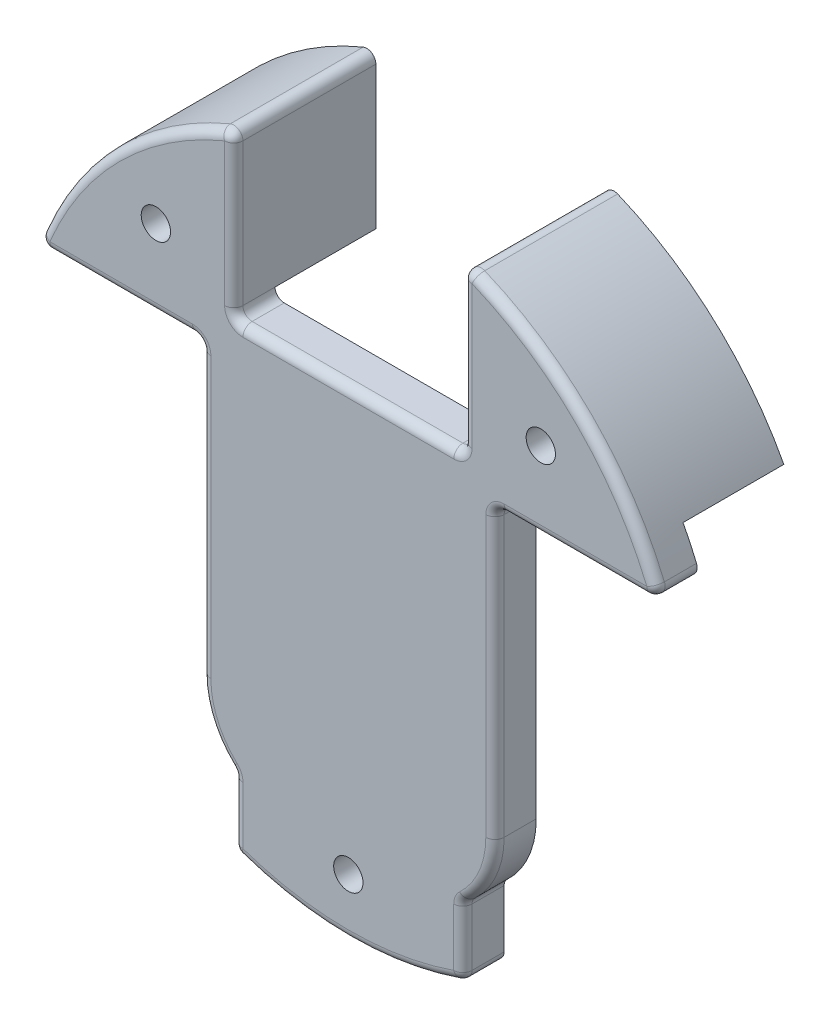
SolidWorks part; units mm, degrees
ref_plane "Front Plane" through (0, 0, 0) normal (0, 0, 1) x (1, 0, 0)
ref_plane "Top Plane" through (0, 0, 0) normal (0, 1, 0) x (1, 0, 0)
ref_plane "Right Plane" through (0, 0, 0) normal (1, 0, 0) x (0, 0, -1)
sketch "草图1" plane through (0, 0, 0) normal (0, 0, 1) x (1, 0, 0)
  circle A0 centre (0, 0) radius 36.25
extrude "凸台-拉伸1" add sketch "草图1" along normal blind 10
sketch "草图2" plane through (0, 0, 0) normal (0, 0, 1) x (1, 0, 0)
  line L1 (-12.5, 36.25) -> (12.5, 36.25)
  line L2 (-12.5, 36.25) -> (-12.5, 16)
  line L3 (-12.5, 16) -> (12.5, 16)
  line L4 (12.5, 36.25) -> (12.5, 16)
extrude "切除-拉伸1" cut sketch "草图2" along normal blind 4.5
sketch "草图3" plane through (0, 0, 0) normal (0, 0, 1) x (1, 0, 0)
  line L1 (-36.25, 12.5) -> (-12.5, 12.5)
  line L2 (-36.25, 12.5) -> (-36.25, -36.25)
  line L3 (-36.25, -36.25) -> (-12.5, -36.25)
  line L4 (-12.5, 12.5) -> (-12.5, -36.25)
  line L5 (12.5, 12.5) -> (36.25, 12.5)
  line L6 (12.5, 12.5) -> (12.5, -36.25)
  line L7 (12.5, -36.25) -> (36.25, -36.25)
  line L8 (36.25, 12.5) -> (36.25, -36.25)
extrude "切除-拉伸2" cut sketch "草图3" along normal blind 4.5
sketch "草图4" plane through (0, 0, 0) normal (0, 0, 1) x (1, 0, 0)
  circle A0 centre (-6, -19) radius 10
extrude "凸台-拉伸2" add sketch "草图4" along normal blind 4.5
sketch "草图5" plane through (0, 0, 0) normal (0, 0, 1) x (1, 0, 0)
  circle A0 centre (6, -19) radius 10
extrude "凸台-拉伸3" add sketch "草图5" along normal blind 4.5
sketch "草图6" plane through (0, 0, 0) normal (0, 0, 1) x (1, 0, 0)
  line L1 (-16, -19) -> (16, -19)
  line L2 (-16, -19) -> (-16, 12.5)
  line L3 (-16, 12.5) -> (16, 12.5)
  line L4 (16, -19) -> (16, 12.5)
extrude "凸台-拉伸4" add sketch "草图6" along normal blind 4.5
sketch "草图7" plane through (0, 0, 4.5) normal (0, 0, -1) x (-1, 0, 0)
  circle A0 centre (0, 0) radius 36.25
extrude "切除-拉伸3" cut sketch "草图7" against normal blind 5.5
sketch "草图8" plane through (0, 0, 0) normal (0, 0, 1) x (1, 0, 0)
  line L1 (-36.25, 17) -> (-12.5, 17)
  line L2 (-36.25, 17) -> (-36.25, 36.25)
  line L3 (-36.25, 36.25) -> (-12.5, 36.25)
  line L4 (-12.5, 17) -> (-12.5, 36.25)
  line L9 (12.5, 17) -> (36.25, 17)
  line L10 (12.5, 17) -> (12.5, 36.25)
  line L11 (12.5, 36.25) -> (36.25, 36.25)
  line L12 (36.25, 17) -> (36.25, 36.25)
extrude "凸台-拉伸5" add sketch "草图8" against normal blind 11
sketch "草图9" plane through (0, 0, 0) normal (0, 0, 1) x (1, 0, 0)
  circle A0 centre (0, 0) radius 36.25
extrude "切除-拉伸4" cut sketch "草图9" against normal blind 11 flip side to cut contours A0
sketch "草图10" plane through (0, 0, 4.5) normal (0, 0, 1) x (1, 0, 0)
  circle A0 centre (-21, 21) radius 0.8
  circle A1 centre (21, 21) radius 0.8
  circle A2 centre (0, -30) radius 0.8
hole_wizard "孔1" positions "草图11" profile "草图12" legacy
sketch "草图11" plane through (0, 0, 4.5) normal (0, 0, 1) x (1, 0, 0)
  point P0 (-21, 21)
  point P3 (21, 21)
sketch "草图12" plane through (-21, 21, 4.5) normal (1, 0, 0) x (0, -1, 0)
  line L0 (0, 0) -> (0, 100)
  line L1 (0, 100) -> (0.8, 100)
  line L2 (0.8, 100) -> (0.8, 14.1)
  line L3 (0.8, 14.1) -> (1.6, 14.1)
  line L4 (1.6, 14.1) -> (1.6, 0)
  line L5 (1.6, 0) -> (0, 0)
  line L6 (0, 110) -> (0, -10) construction
  dimension "直径" = 1.6
  dimension "深度" = 100
  dimension "柱坑直径" = 3.2
  dimension "柱坑深度" = 14.1
hole_wizard "孔2" positions "草图13" profile "草图14" legacy
sketch "草图13" plane through (0, 0, 4.5) normal (0, 0, 1) x (1, 0, 0)
  point P0 (0, -30)
sketch "草图14" plane through (0, -30, 4.5) normal (1, 0, 0) x (0, -1, 0)
  line L0 (0, 0) -> (0, 100)
  line L1 (0, 100) -> (0.8, 100)
  line L2 (0.8, 100) -> (0.8, 3.1)
  line L3 (0.8, 3.1) -> (1.6, 3.1)
  line L4 (1.6, 3.1) -> (1.6, 0)
  line L5 (1.6, 0) -> (0, 0)
  line L6 (0, 110) -> (0, -10) construction
  dimension "直径" = 1.6
  dimension "深度" = 100
  dimension "柱坑直径" = 3.2
  dimension "柱坑深度" = 3.1
fillet "圆角1" radius 1 12 edges at (-16, 12.5, 2.25) (16, 12.5, 2.25) (12.5, 16, 2.25) (-12.5, 34.0266, -3.25) (-12.5, 16, 2.25) (12.5, 34.0266, -3.25) (-12.5, -34.0266, 2.25) (-34.0266, 12.5, 2.25) (12.5, -34.0266, 2.25) (34.0266, 12.5, 2.25) (-12.5, -26.5993, 2.25) (12.5, -26.5993, 2.25)
fillet "圆角2" radius 1 24 edges at (-16.2929, 12.2071, 4.5) (-24.7812, 12.5, 4.5) (-33.394, 12.9446, 4.5) (0, -36.25, 4.5) (-12.9446, 33.394, 4.5) (-12.5, 24.7812, 4.5) (-12.2071, 16.2929, 4.5) (0, 16, 4.5) (12.2071, 16.2929, 4.5) (12.5, 24.7812, 4.5) (12.9446, 33.394, 4.5) (33.394, 12.9446, 4.5) (24.7812, 12.5, 4.5) (16.2929, 12.2071, 4.5) (16, -3.75, 4.5) (15.1701, -22.9886, 4.5) (12.583, -26.6479, 4.5) (12.5, -30.184, 4.5) (12.3143, -33.9018, 4.5) (-12.3143, -33.9018, 4.5) (-12.5, -30.184, 4.5) (-12.583, -26.6479, 4.5) (-15.1701, -22.9886, 4.5) (-16, -3.75, 4.5)
